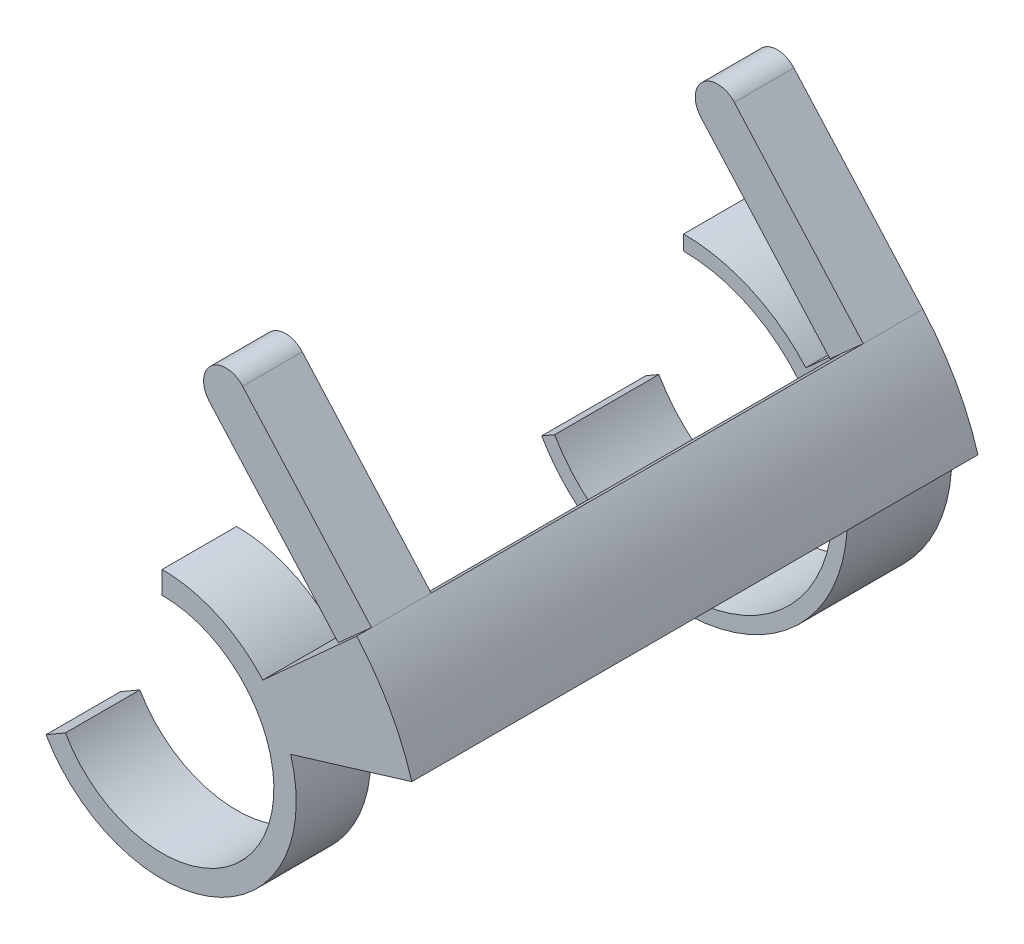
SolidWorks part; units mm, degrees
ref_plane "Front Plane" through (0, 0, 0) normal (0, 0, 1) x (1, 0, 0)
ref_plane "Top Plane" through (0, 0, 0) normal (0, 1, 0) x (1, 0, 0)
ref_plane "Right Plane" through (0, 0, 0) normal (1, 0, 0) x (0, 0, -1)
sketch "Sketch1" plane through (0, 0, 0) normal (0, 0, 1) x (1, 0, 0)
  line L0 (-9.5263, -5.5) -> (-8.6603, -5)
  line L1 (0, 10) -> (0, 11)
  arc A0 (-8.6603, -5) -> (0, 10) centre (0, 0) ccw
  arc A1 (-9.5263, -5.5) -> (0, 11) centre (0, 0) ccw
  dimension "D1" = 22
  dimension "D2" = 20
  dimension "D3" = 120
extrude "Boss-Extrude1" add sketch "Sketch1" along normal blind 7
sketch "Sketch3" plane through (0, 0, 7) normal (0, 0, 1) x (1, 0, 0)
  line L0 (8.2074, 7.3238) -> (13.0573, 11.6515)
  line L1 (10.5336, 3.169) -> (16.758, 5.0416)
  arc A0 (10.5336, 3.169) -> (8.2074, 7.3238) centre (0, 0) ccw
  arc A1 (16.758, 5.0416) -> (13.0573, 11.6515) centre (0, 0) ccw
  arc A2 (-9.5263, -5.5) -> (0, 11) centre (0, 0) ccw construction
  dimension "D1" = 35
  dimension "D2" = 25
extrude "Boss-Extrude2" add sketch "Sketch3" against normal blind 3
sketch "Sketch4" plane through (0, 0, 7) normal (0, 0, 1) x (1, 0, 0)
  line L0 (13.0573, 11.6515) -> (11.565, 10.3199)
  line L1 (14.8428, 4.4655) -> (16.758, 5.0416)
  arc A0 (14.8428, 4.4655) -> (11.565, 10.3199) centre (0, 0) ccw
  arc A1 (16.758, 5.0416) -> (13.0573, 11.6515) centre (0, 0) ccw
  arc A2 (16.758, 5.0416) -> (13.0573, 11.6515) centre (0, 0) ccw construction
  dimension "D1" = 31
extrude "Boss-Extrude3" add sketch "Sketch4" along normal blind 30
sketch "Sketch5" plane through (0, 0, 37) normal (0, 0, 1) x (1, 0, 0)
  line L0 (0, 9) -> (0, 7.5)
  line L1 (-6.4952, -3.75) -> (-7.7942, -4.5)
  arc A0 (-6.4952, -3.75) -> (0, 7.5) centre (0, 0) ccw
  arc A1 (-7.7942, -4.5) -> (0, 9) centre (0, 0) ccw
  dimension "D1" = 15
  dimension "D2" = 18
extrude "Boss-Extrude4" add sketch "Sketch5" along normal blind 5 separate body
sketch "Sketch6" plane through (0, 0, 37) normal (0, 0, 1) x (1, 0, 0)
  line L0 (6.7563, 5.9457) -> (13.0573, 11.6515)
  line L1 (8.6261, 2.567) -> (16.758, 5.0416)
  arc A0 (16.758, 5.0416) -> (13.0573, 11.6515) centre (0, 0) ccw
  arc A1 (8.6261, 2.567) -> (6.7563, 5.9457) centre (0, 0) ccw
extrude "Boss-Extrude5" add sketch "Sketch6" along normal blind 5
sketch "Sketch7" plane through (0, 0, 4) normal (0, 0, -1) x (-1, 0, 0)
  line L6 (0, 0) -> (-15.2696, 8.5492) construction
  line L7 (-10.8189, 9.6541) -> (-13.0573, 11.6515)
  line L8 (-10.8189, 9.6541) -> (-2.1634, 19.3538)
  line L9 (-13.0573, 11.6515) -> (-4.4018, 21.3512)
  arc A1 (-13.0573, 11.6515) -> (-16.758, 5.0416) centre (0, 0) ccw construction
  arc A3 (-4.4018, 21.3512) -> (-2.1634, 19.3538) centre (-3.2826, 20.3525) cw
extrude "Boss-Extrude6" add sketch "Sketch7" against normal blind 4
sketch "Sketch8" plane through (0, 0, 37) normal (0, 0, -1) x (-1, 0, 0)
  line L2 (-10.8189, 9.6541) -> (-13.0573, 11.6515)
  line L3 (-4.4018, 21.3512) -> (-13.0573, 11.6515)
  line L4 (-10.8189, 9.6541) -> (-2.1634, 19.3538)
  arc A0 (-2.1634, 19.3538) -> (-4.4018, 21.3512) centre (-3.2826, 20.3525) ccw
  arc A1 (-2.1634, 19.3538) -> (-4.4018, 21.3512) centre (-3.2826, 20.3525) ccw construction
extrude "Boss-Extrude7" add sketch "Sketch8" against normal blind 4 separate body
